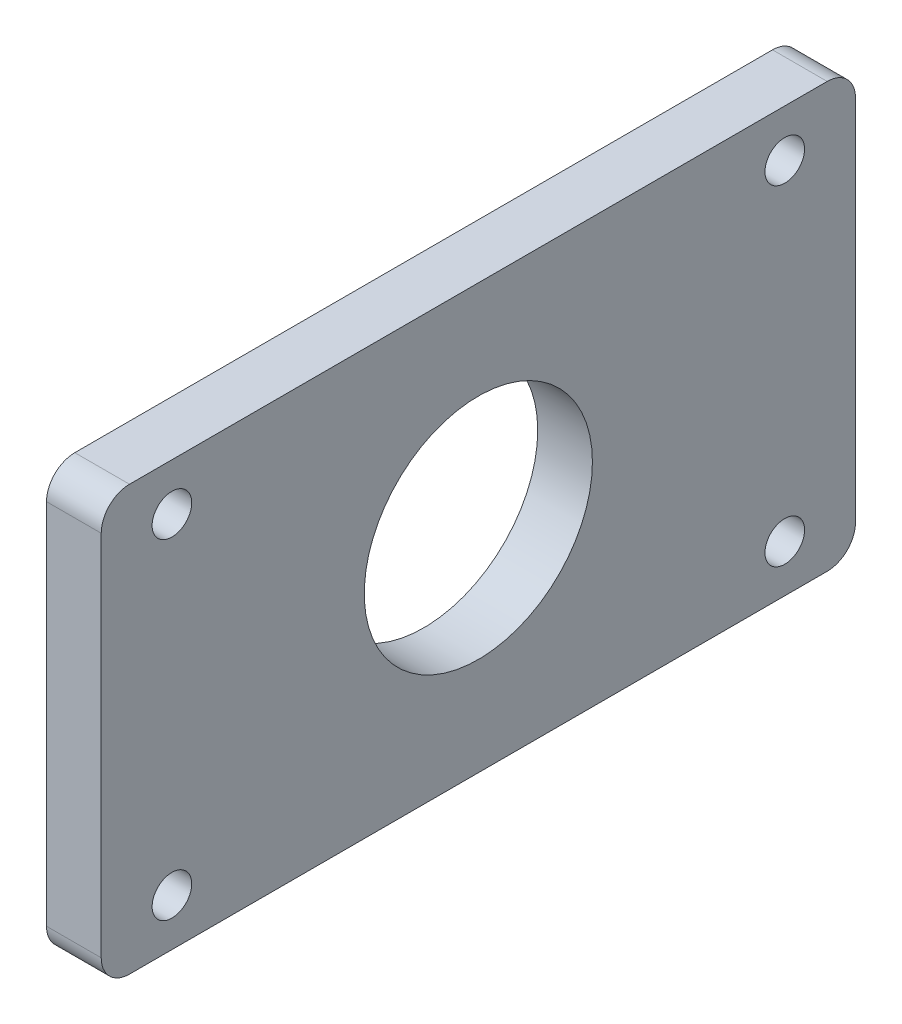
SolidWorks part; units mm, degrees
material "MC901"
ref_plane "正面" through (0, 0, 0) normal (0, 0, 1) x (1, 0, 0)
ref_plane "平面" through (0, 0, 0) normal (0, 1, 0) x (1, 0, 0)
ref_plane "右側面" through (0, 0, 0) normal (1, 0, 0) x (0, 0, -1)
sketch "ｽｹｯﾁ1" plane through (0, 0, 0) normal (1, 0, 0) x (0, 0, -1)
  line L0 (0, 22.5) -> (0, 0) construction
  line L1 (-40, 22.5) -> (40, 22.5)
  line L2 (-40, 22.5) -> (-40, -22.5)
  line L3 (-40, -22.5) -> (40, -22.5)
  line L4 (40, 22.5) -> (40, -22.5)
  line L5 (-40, 22.5) -> (40, -22.5) construction
  line L6 (-40, -22.5) -> (40, 22.5) construction
  line L7 (-32.5, 17.5) -> (32.5, 17.5) construction
  line L8 (-32.5, 17.5) -> (-32.5, -17.5) construction
  line L9 (-32.5, -17.5) -> (32.5, -17.5) construction
  line L10 (32.5, 17.5) -> (32.5, -17.5) construction
  line L11 (-32.5, 17.5) -> (32.5, -17.5) construction
  line L12 (-32.5, -17.5) -> (32.5, 17.5) construction
  line L13 (0, 0) -> (40, 0) construction
  circle A0 centre (0, 0) radius 12.1
  circle A1 centre (32.5, 17.5) radius 2.1
  circle A2 centre (32.5, -17.5) radius 2.1
  circle A3 centre (-32.5, 17.5) radius 2.1
  circle A4 centre (-32.5, -17.5) radius 2.1
  point P0 (0, 0)
  dimension "D3" = 24.2
  dimension "D6" = 4.2
  dimension "D1" = 45
  dimension "D2" = 80
  dimension "D4" = 35
  dimension "D5" = 65
extrude "ﾎﾞｽ - 押し出し1" add sketch "ｽｹｯﾁ1" along normal blind 5.8
fillet "ﾌｨﾚｯﾄ1" radius 3 4 edges at (2.9, -22.5, -40) (2.9, 22.5, -40) (2.9, -22.5, 40) (2.9, 22.5, 40)
